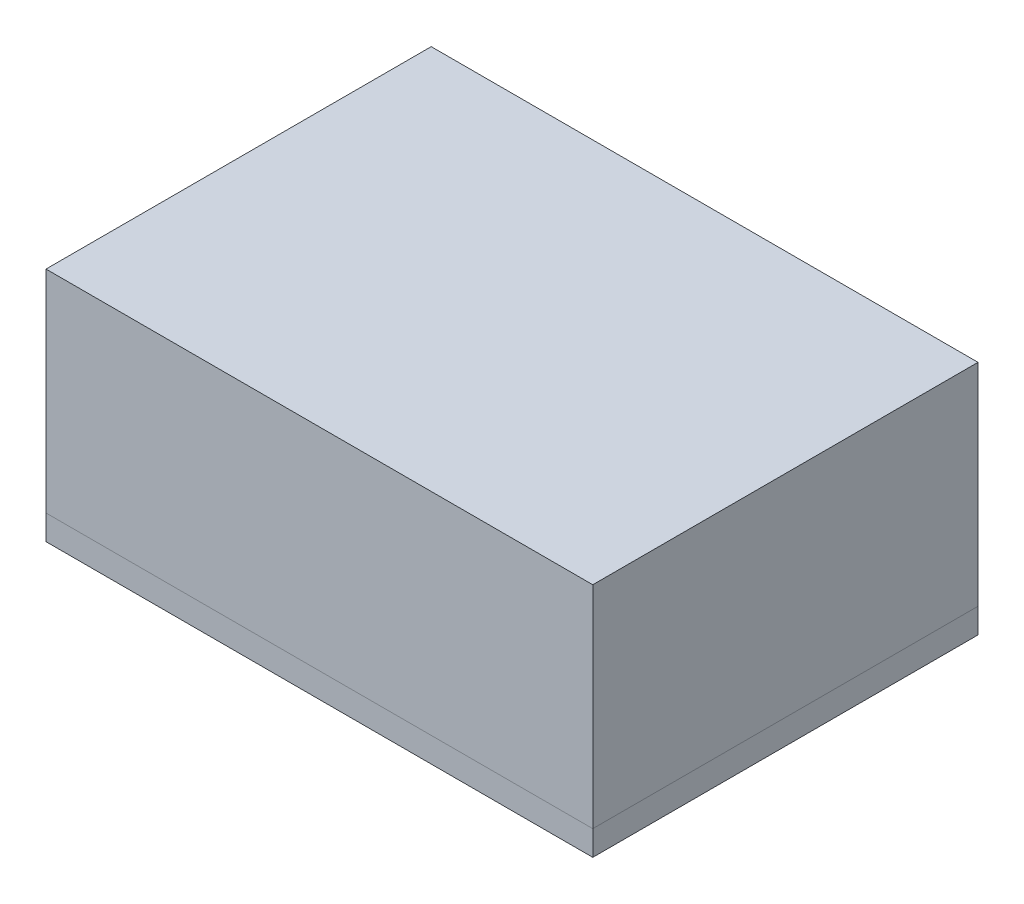
SolidWorks part; units mm, degrees
ref_plane "前视基准面" through (0, 0, 0) normal (0, 0, 1) x (1, 0, 0)
ref_plane "上视基准面" through (0, 0, 0) normal (0, 1, 0) x (1, 0, 0)
ref_plane "右视基准面" through (0, 0, 0) normal (1, 0, 0) x (0, 0, -1)
sketch "草图1" plane through (0, 0, 0) normal (0, 1, 0) x (1, 0, 0)
  line L1 (0, 0) -> (22, 0)
  line L2 (0, 0) -> (0, -15.5)
  line L3 (0, -15.5) -> (22, -15.5)
  line L4 (22, 0) -> (22, -15.5)
  dimension "D1" = 22
  dimension "D2" = 15.5
extrude "凸台-拉伸1" add sketch "草图1" along normal blind 1
sketch "草图2" plane through (0, 1, 0) normal (0, 1, 0) x (1, 0, 0)
  line L0 (22, 0) -> (0, 0) construction
  line L1 (4.95, 0) -> (0, 0)
  line L2 (4.95, 0) -> (4.95, -1)
  line L3 (4.95, -1) -> (1, -1)
  line L4 (0, 0) -> (0, -1.5)
  line L5 (0, 0) -> (0, -15.5) construction
  line L6 (11, 0) -> (11, -15.5) construction
  line L7 (0, -15.5) -> (22, -15.5) construction
  line L12 (22, -1.5) -> (22, -15.5)
  line L14 (0, -1.5) -> (0, -15.5)
  line L15 (0, -15.5) -> (1.5, -15.5)
  line L16 (1, -1) -> (1, -14.5)
  line L17 (1.5, -15.5) -> (20.5, -15.5)
  line L19 (1, -14.5) -> (21, -14.5)
  line L20 (11, -15.5) -> (11, -14.5)
  line L21 (22, 0) -> (22, -1.5)
  line L22 (17.05, 0) -> (22, 0)
  line L23 (17.05, 0) -> (17.05, -1)
  line L24 (17.05, -1) -> (21, -1)
  line L25 (21, -1) -> (21, -14.5)
  line L26 (22, -15.5) -> (20.5, -15.5)
  line M16 (0, 0) -> (0, -15.5)
  line M17 (0, -15.5) -> (22, -15.5)
  line M18 (22, -15.5) -> (22, 0)
  line M19 (22, 0) -> (0, 0)
  dimension "D1" = 4.95
  dimension "D2" = 1
  dimension "D3" = 1
  dimension "D4" = 1
extrude "凸台-拉伸2" add sketch "草图2" along normal blind 5 contours L20 L19 L16 L3 L2 M17 M19 M16 | L24 L25 L19 L20 L17 L23 M17 M18 M19
sketch "草图3" plane through (0, 6, 0) normal (0, 1, 0) x (1, 0, 0)
  line L0 (0, -15.5) -> (22, -15.5)
  line L1 (22, -15.5) -> (22, 0)
  line L2 (22, 0) -> (0, 0)
  line L3 (0, 0) -> (0, -15.5)
  line L4 (1, -14.5) -> (21, -14.5)
  line L5 (21, -14.5) -> (21, -1)
  line L6 (21, -1) -> (1, -1)
  line L7 (4.95, -1) -> (1, -1) construction
  line L8 (1, -1) -> (1, -14.5) construction
  line L9 (1, -1) -> (1, -14.5)
extrude "凸台-拉伸3" add sketch "草图3" along normal blind 2
sketch "草图4" plane through (0, 8, 0) normal (0, 1, 0) x (1, 0, 0)
  line L1 (0, 0) -> (22, 0)
  line L2 (0, 0) -> (0, -15.5)
  line L3 (0, -15.5) -> (22, -15.5)
  line L4 (22, 0) -> (22, -15.5)
extrude "凸台-拉伸4" add sketch "草图4" along normal blind 1.5
ref_plane "基准面1" through (0, 1, 0) normal (0, -1, 0) x (-1, 0, 0)
split "分割1" trim tools "基准面1" bodies to split 109 resulting bodies 110 111
split "分割2" trim tools "基准面1" bodies to split 111 110 resulting bodies 112 113
